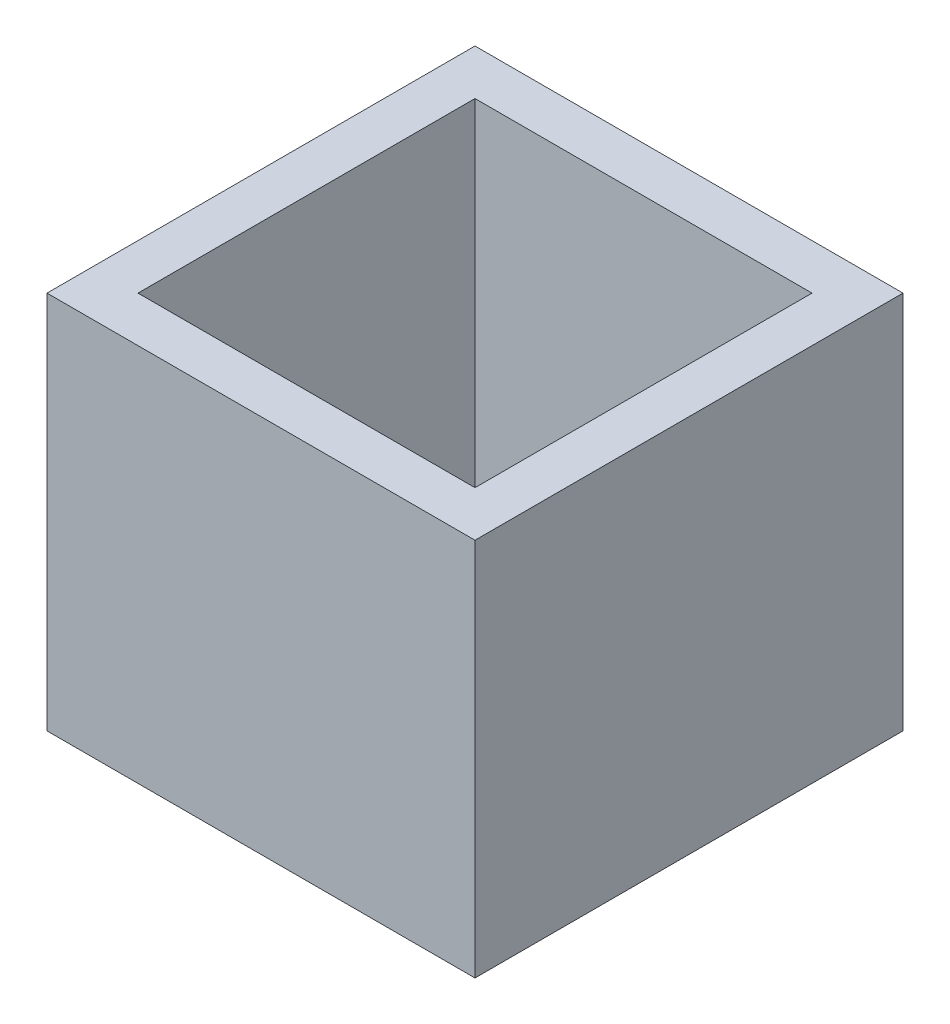
SolidWorks part; units mm, degrees
ref_plane "Front Plane" through (0, 0, 0) normal (0, 0, 1) x (1, 0, 0)
ref_plane "Top Plane" through (0, 0, 0) normal (0, 1, 0) x (1, 0, 0)
ref_plane "Right Plane" through (0, 0, 0) normal (1, 0, 0) x (0, 0, -1)
sketch "Sketch1" plane through (0, 0, 0) normal (0, 1, 0) x (1, 0, 0)
  line L1 (-10.16, -10.16) -> (10.16, -10.16)
  line L2 (-10.16, -10.16) -> (-10.16, 10.16)
  line L3 (-10.16, 10.16) -> (10.16, 10.16)
  line L4 (10.16, -10.16) -> (10.16, 10.16)
  line L5 (-10.16, -10.16) -> (10.16, 10.16) construction
  line L6 (-10.16, 10.16) -> (10.16, -10.16) construction
  point P0 (0, 0)
  dimension "D1" = 20.32
  dimension "D2" = 20.32
extrude "Boss-Extrude1" add sketch "Sketch1" along normal blind 18
sketch "Sketch2" plane through (0, 18, 0) normal (0, 1, 0) x (1, 0, 0)
  line L1 (-8, -8) -> (8, -8)
  line L2 (-8, -8) -> (-8, 8)
  line L3 (-8, 8) -> (8, 8)
  line L4 (8, -8) -> (8, 8)
  line L5 (-8, -8) -> (8, 8) construction
  line L6 (-8, 8) -> (8, -8) construction
  point P0 (0, 0)
  dimension "D1" = 16
  dimension "D2" = 16
extrude "Cut-Extrude1" cut sketch "Sketch2" against normal blind 16.5
